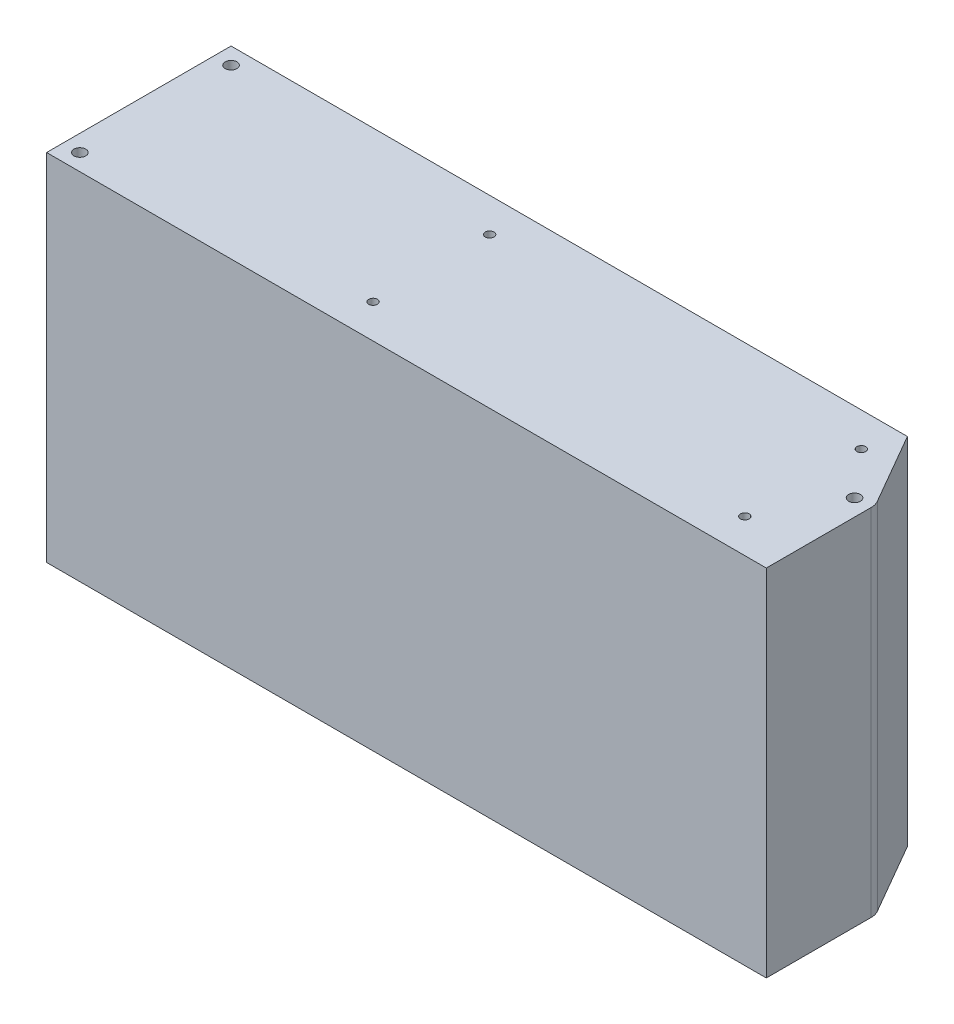
SolidWorks part; units mm, degrees
ref_plane "Front Plane" through (0, 0, 0) normal (0, 0, 1) x (1, 0, 0)
ref_plane "Top Plane" through (0, 0, 0) normal (0, 1, 0) x (1, 0, 0)
ref_plane "Right Plane" through (0, 0, 0) normal (1, 0, 0) x (0, 0, -1)
sketch "Sketch1" plane through (0, 0, 0) normal (0, 1, 0) x (1, 0, 0)
  line L0 (-196.4236, 43.2594) -> (-196.4236, -43.2594) construction
  line L1 (-205.9486, -52.7844) -> (205.9486, -52.7844)
  line L2 (-205.9486, -52.7844) -> (-205.9486, 52.7844)
  line L3 (-205.9486, 52.7844) -> (181.1345, 52.7844)
  line L4 (205.9486, -52.7844) -> (205.9486, 7.253)
  line L5 (-205.9486, -52.7844) -> (205.9486, 52.7844) construction
  line L6 (-205.9486, 52.7844) -> (205.9486, -52.7844) construction
  line L7 (-196.4236, 0) -> (0, 0) construction
  line L8 (0, 0) -> (196.4236, 0) construction
  line L9 (204.6725, 12.0155) -> (181.1345, 52.7844)
  line L10 (181.1345, 52.7844) -> (205.9486, 52.7844) construction
  line L11 (205.9486, 52.7844) -> (205.9486, 7.253) construction
  circle A0 centre (-196.4236, 43.2594) radius 3.3782
  circle A1 centre (-196.4236, -43.2594) radius 3.3782
  circle A2 centre (196.4236, 7.253) radius 3.3782
  circle A3 centre (174.1986, 33.3375) radius 2.5
  circle A4 centre (-38.5264, 33.3375) radius 2.5
  circle A5 centre (-38.5264, -33.3375) radius 2.5
  circle A6 centre (174.1986, -33.3375) radius 2.5
  arc A7 (205.9486, 7.253) -> (204.6725, 12.0155) centre (196.4236, 7.253) ccw
  point P0 (0, 0)
  point P27 (0, 0)
  dimension "D6" = 6.7564
  dimension "D7" = 5
  dimension "D1" = 86.5187
  dimension "D2" = 394.4937
  dimension "D3" = 396.0813
  dimension "D4" = 66.675
  dimension "D5" = 212.725
  dimension "D8" = 9.525
  dimension "D9" = 9.525
  dimension "D10" = 30
  dimension "D11" = 22.225
extrude "Boss-Extrude1" add sketch "Sketch1" along normal blind 203.2
